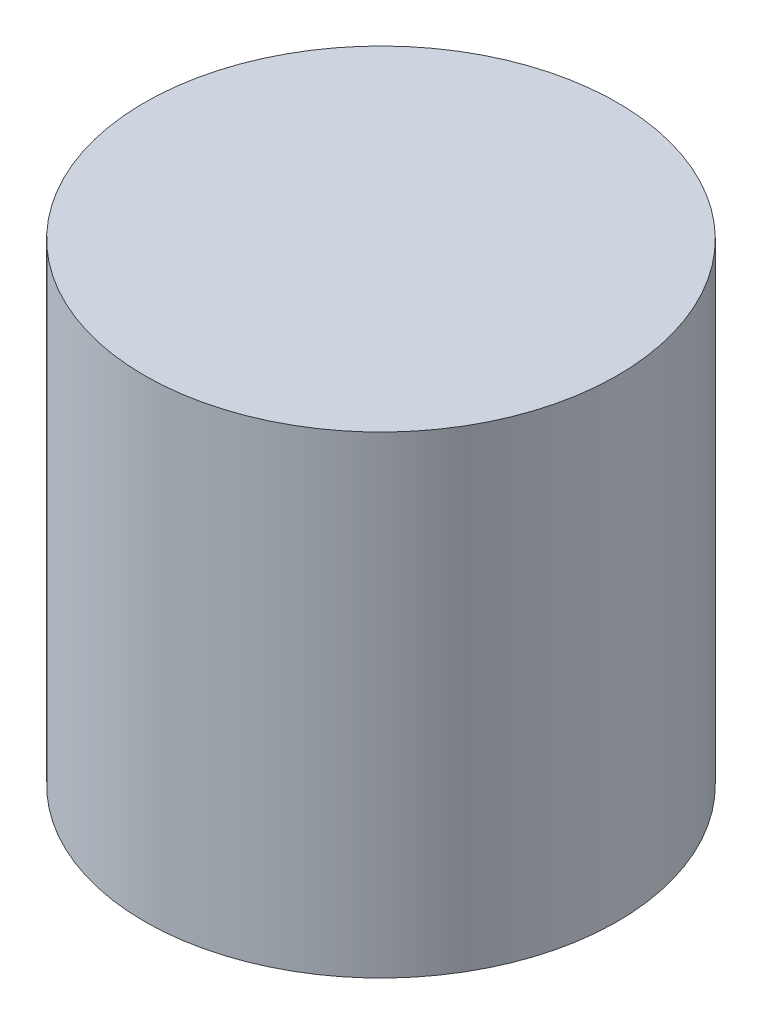
SolidWorks part; units mm, degrees
ref_plane "Front Plane" through (0, 0, 0) normal (0, 0, 1) x (1, 0, 0)
ref_plane "Top Plane" through (0, 0, 0) normal (0, 1, 0) x (1, 0, 0)
ref_plane "Right Plane" through (0, 0, 0) normal (1, 0, 0) x (0, 0, -1)
sketch "Sketch1" plane through (0, 0, 0) normal (0, 1, 0) x (1, 0, 0)
  circle A0 centre (0, 0) radius 18
  dimension "D1" = 36
extrude "Boss-Extrude1" add sketch "Sketch1" along normal blind 36
